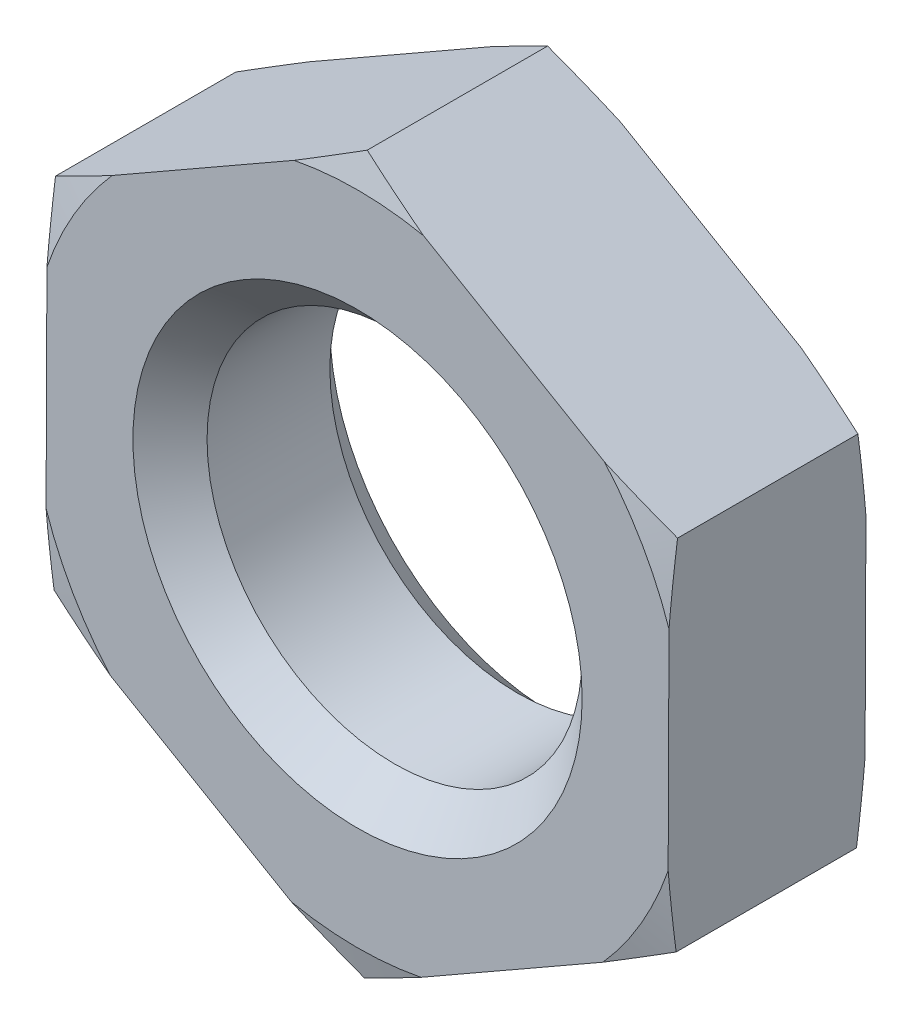
SolidWorks part; units mm, degrees
extrude "基体-拉伸" add sketch "草图1" along normal blind 2.1
sketch "草图1" plane through (0, 0, 0) normal (0, 0, 1) x (1, 0, 0)
  line L0 (-26.8088, 0) -> (37.1748, 0) construction
  line L1 (0, 25.0215) -> (0, -25.0215) construction
  line L3 (0.0151, 3.83) -> (-3.3093, 1.928)
  line L4 (-3.3093, 1.928) -> (-3.3244, -1.9019)
  line L5 (-3.3244, -1.9019) -> (-0.0151, -3.83)
  line L6 (-0.0151, -3.83) -> (3.3093, -1.928)
  line L7 (3.3093, -1.928) -> (3.3244, 1.9019)
  line L8 (3.3244, 1.9019) -> (0.0151, 3.83)
  circle A0 centre (0, 0) radius 3.3169 construction
  circle A1 centre (0, 0) radius 2
  dimension "D" = 4
  dimension "e" = 7.66
cosmetic thread "装饰螺纹线1" parameters "D2"=4
material "A2-70级"
ref_plane "基准面1" through (0, 0, 0) normal (0, 0, 1) x (1, 0, 0)
ref_plane "基准面2" through (0, 0, 0) normal (0, 1, 0) x (1, 0, 0)
ref_plane "基准面3" through (0, 0, 0) normal (1, 0, 0) x (0, 0, -1)
sketch "尺寸草图" plane through (0, 0, 0) normal (0, 0, 1) x (1, 0, 0)
  line L0 (0, 0) -> (32.8249, 0)
  line L1 (32.8249, 0) -> (37.4249, 0)
  line L2 (37.4249, 0) -> (43.3249, 0)
  line L3 (-3.8095, 0) -> (0, 0)
  point P3 (4, 0)
  point P4 (1.5, 0)
  point P5 (7.66, 0)
  point P6 (3.2, 0)
  point P7 (6.4, 0)
  point P8 (7, 0)
  dimension "D" = 4
  dimension "e" = 7.66
  dimension "P" = 1.5
  dimension "m" = 3.2
  dimension "mw" = 6.4
  dimension "s" = 7
  dimension "da" = 4.6
  dimension "dw" = 5.9
  dimension "D1" = 3.8095
sketch "草图2" plane through (0, 0, 0) normal (0, 0, -1) x (-1, 0, 0)
  circle A0 centre (0, 0) radius 3.5
  circle A1 centre (0, 0) radius 2 construction
  dimension "s" = 7
extrude "切除-拉伸1" cut sketch "草图2" against normal through all draft 75 flip side to cut
sketch "草图3" plane through (0, 0, 2.1) normal (0, 0, 1) x (1, 0, 0)
  circle A0 centre (0, 0) radius 3.5
  dimension "D1" = 7
extrude "切除-拉伸2" cut sketch "草图3" against normal through all draft 75 flip side to cut
chamfer "倒角1" distance 0.3952 angle 45 2 edges at (2, 0, 0) (2, 0, 2.1)
sketch "草图4" plane through (-1.6697, -2.866, 0) normal (-0.5034, -0.8641, 0) x (0.8641, -0.5034, 0)
  line L0 (-1.1173, 0) -> (1.1173, 0) construction
  line L1 (-5.3624, 4.2587) -> (4.9542, 4.2587)
  line L2 (-5.3624, 4.2587) -> (-5.3624, 2.1)
  line L3 (-5.3624, 2.1) -> (4.9542, 2.1)
  line L4 (4.9542, 4.2587) -> (4.9542, 2.1)
  dimension "D1" = 2.1
equation "\"e@草图1\" = \"e@尺寸草图\""
equation "\"D1@尺寸草图\" = \"D@尺寸草图\" / 1.05"
equation "\"D@草图1\" = \"D@尺寸草图\""
equation "\"D1@草图3\" = \"s@尺寸草图\""
equation "\"s@草图2\" = \"s@尺寸草图\""
equation "\"D2@装饰螺纹线1\" =\"D@尺寸草图\""
equation "\"D1@倒角1\" =  ( \"da@尺寸草图\" - \"D1@尺寸草图\" )  / 2"
